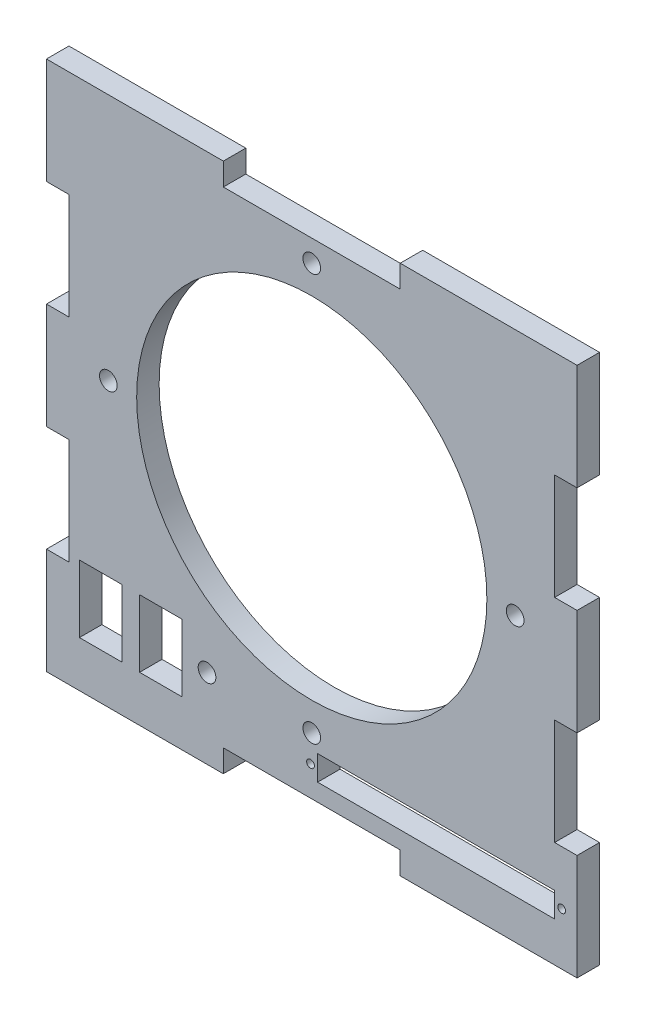
SolidWorks part; units mm, degrees
ref_plane "Front Plane" through (0, 0, 0) normal (0, 0, 1) x (1, 0, 0)
ref_plane "Top Plane" through (0, 0, 0) normal (0, 1, 0) x (1, 0, 0)
ref_plane "Right Plane" through (0, 0, 0) normal (1, 0, 0) x (0, 0, -1)
sketch "Sketch2" plane through (0, 0, 0) normal (0, 0, 1) x (1, 0, 0)
  line L0 (-7.2056, 187.8918) -> (-7.2056, 157.8918)
  line L1 (-0.8556, 67.8918) -> (-7.2056, 67.8918)
  line L2 (-7.2056, 67.8918) -> (-7.2056, 37.8918)
  line L3 (-7.2056, 157.8918) -> (-0.8556, 157.8918)
  line L4 (67.7944, 94.2853) -> (67.7944, 207.1222) construction
  line L5 (-7.2056, 187.8918) -> (42.7944, 187.8918)
  line L6 (42.7944, 187.8918) -> (42.7944, 181.5418)
  line L7 (42.7944, 181.5418) -> (92.7944, 181.5418)
  line L8 (92.7944, 181.5418) -> (92.7944, 187.8918)
  line L9 (92.7944, 187.8918) -> (142.7944, 187.8918)
  line L10 (142.7944, 67.8918) -> (142.7944, 37.8918)
  line L11 (136.4444, 67.8918) -> (142.7944, 67.8918)
  line L12 (136.4444, 97.8918) -> (136.4444, 67.8918)
  line L13 (142.7944, 97.8918) -> (136.4444, 97.8918)
  line L14 (-0.8556, 157.8918) -> (-0.8556, 127.8918)
  line L15 (-0.8556, 127.8918) -> (-7.2056, 127.8918)
  line L16 (-7.2056, 127.8918) -> (-7.2056, 97.8918)
  line L17 (-7.2056, 97.8918) -> (-0.8556, 97.8918)
  line L18 (-0.8556, 97.8918) -> (-0.8556, 67.8918)
  line L19 (142.7944, 127.8918) -> (142.7944, 97.8918)
  line L20 (136.4444, 127.8918) -> (142.7944, 127.8918)
  line L21 (136.4444, 157.8918) -> (136.4444, 127.8918)
  line L22 (142.7944, 157.8918) -> (136.4444, 157.8918)
  line L23 (142.7944, 187.8918) -> (142.7944, 157.8918)
  line L24 (-7.2056, 37.8918) -> (42.7944, 37.8918)
  line L25 (42.7944, 37.8918) -> (42.7944, 44.2418)
  line L26 (42.7944, 44.2418) -> (92.7944, 44.2418)
  line L27 (92.7944, 44.2418) -> (92.7944, 37.8918)
  line L28 (92.7944, 37.8918) -> (142.7944, 37.8918)
  line L29 (57.7635, 60.3918) -> (87.4302, 60.3918) construction
  line L30 (19.1118, 69.8918) -> (31.1118, 69.8918)
  line L31 (19.1118, 69.8918) -> (19.1118, 50.8918)
  line L32 (19.1118, 50.8918) -> (31.1118, 50.8918)
  line L33 (31.1118, 69.8918) -> (31.1118, 50.8918)
  line L34 (2.1118, 69.8918) -> (14.1118, 69.8918)
  line L35 (2.1118, 69.8918) -> (2.1118, 50.8918)
  line L36 (2.1118, 50.8918) -> (14.1118, 50.8918)
  line L37 (14.1118, 69.8918) -> (14.1118, 50.8918)
  line L39 (69.4444, 56.161) -> (136.4444, 56.161)
  line L40 (69.4444, 56.161) -> (69.4444, 49.161)
  line L41 (69.4444, 49.161) -> (136.4444, 49.161)
  line L42 (-0.8556, 60.3918) -> (38.1816, 60.3918) construction
  line L43 (19.1118, 60.3918) -> (31.1118, 60.3918) construction
  line L44 (2.1118, 60.3918) -> (14.1118, 60.3918) construction
  line L45 (136.4444, 56.161) -> (136.4444, 49.161)
  circle A0 centre (67.7944, 117.8918) radius 49.5
  circle A1 centre (38.1816, 60.3918) radius 2.5
  circle A2 centre (10.2944, 117.8918) radius 2.5
  circle A3 centre (67.7944, 60.3918) radius 2.5
  circle A4 centre (125.2944, 117.8918) radius 2.5
  circle A5 centre (67.7944, 175.3918) radius 2.5
  circle A6 centre (67.4444, 52.661) radius 1.095
  circle A7 centre (138.4444, 52.661) radius 1.095
  point P45 (25.1118, 50.8918)
  point P46 (25.1118, 69.8918)
  point P67 (69.4444, 52.661)
  dimension "D2" = 99
  dimension "D4" = 30
  dimension "D6" = 50
  dimension "D7" = 5
  dimension "D11" = 30
  dimension "D10" = 12
  dimension "D21" = 5
  dimension "D23" = 2.19
  dimension "D24" = 2.19
  dimension "D3" = 30
  dimension "D5" = 50
  dimension "D8" = 6.35
  dimension "D9" = 6.35
  dimension "D12" = 30
  dimension "D13" = 30
  dimension "D14" = 6.35
  dimension "D15" = 6.35
  dimension "D16" = 19
  dimension "D17" = 12
  dimension "D18" = 19
  dimension "D19" = 67
  dimension "D20" = 7
  dimension "D22" = 16.15
  dimension "D25" = 2
  dimension "D26" = 2
  dimension "D27" = 3.5
  dimension "D28" = 3.5
  dimension "D29" = 5
extrude "Boss-Extrude1" add sketch "Sketch2" along normal blind 6.35
